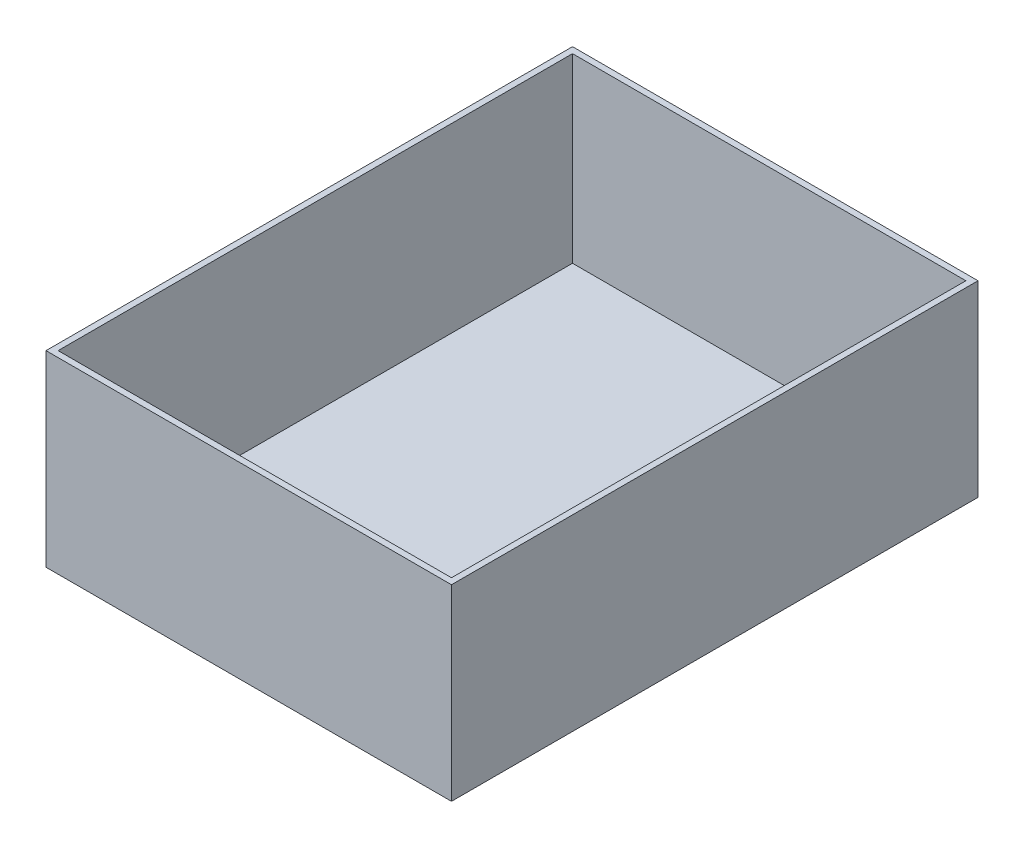
SolidWorks part; units mm, degrees
material "Glass"
ref_plane "Front Plane" through (0, 0, 0) normal (0, 0, 1) x (1, 0, 0)
ref_plane "Top Plane" through (0, 0, 0) normal (0, 1, 0) x (1, 0, 0)
ref_plane "Right Plane" through (0, 0, 0) normal (1, 0, 0) x (0, 0, -1)
sketch "Sketch1" plane through (0, 0, 0) normal (0, 1, 0) x (1, 0, 0)
  line L1 (155.0379, -278.1793) -> (320.1379, -278.1793)
  line L2 (155.0379, -278.1793) -> (155.0379, -62.2793)
  line L3 (155.0379, -62.2793) -> (320.1379, -62.2793)
  line L4 (320.1379, -278.1793) -> (320.1379, -62.2793)
  dimension "D1" = 215.9
  dimension "D2" = 165.1
extrude "Boss-Extrude1" add sketch "Sketch1" along normal blind 76.2 contours L4 L3 L2 L1
shell "Shell3" thickness 2.54
